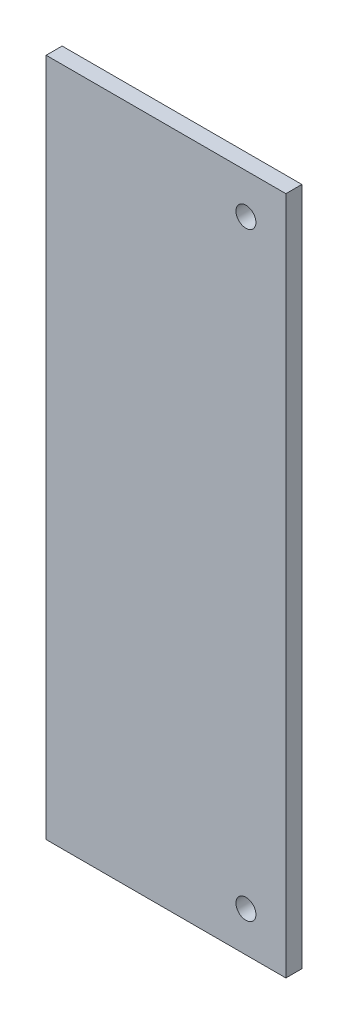
SolidWorks part; units mm, degrees
ref_plane "Front" through (0, 0, 0) normal (0, 0, 1) x (1, 0, 0)
ref_plane "Top" through (0, 0, 0) normal (0, 1, 0) x (1, 0, 0)
ref_plane "Right" through (0, 0, 0) normal (1, 0, 0) x (0, 0, -1)
sketch "Sketch1" plane through (0, 0, 0) normal (0, 0, 1) x (1, 0, 0)
  line L1 (-60, 170) -> (0, 170)
  line L2 (-60, 170) -> (-60, 0)
  line L3 (-60, 0) -> (0, 0)
  line L6 (0, 170) -> (0, 0)
  dimension "D2" = 60
  dimension "D3" = 170
extrude "Boss-Extrude1" add sketch "Sketch1" along normal blind 4
sketch "Sketch2" plane through (0, 0, 0) normal (0, 0, -1) x (-1, 0, 0)
  line L0 (10, 0) -> (10, 10) construction
  line L1 (60, 0) -> (0, 0) construction
  line L2 (10, 10) -> (0, 10) construction
  line L3 (0, 0) -> (0, 170) construction
  line L4 (10, 160) -> (0, 160) construction
  line L5 (10, 160) -> (10, 170) construction
  line L6 (0, 170) -> (60, 170) construction
  circle A0 centre (10, 10) radius 2.5
  circle A1 centre (10, 160) radius 2.5
  dimension "D1" = 5
  dimension "D2" = 10
  dimension "D3" = 10
extrude "Cut-Extrude1" cut sketch "Sketch2" against normal up to next
